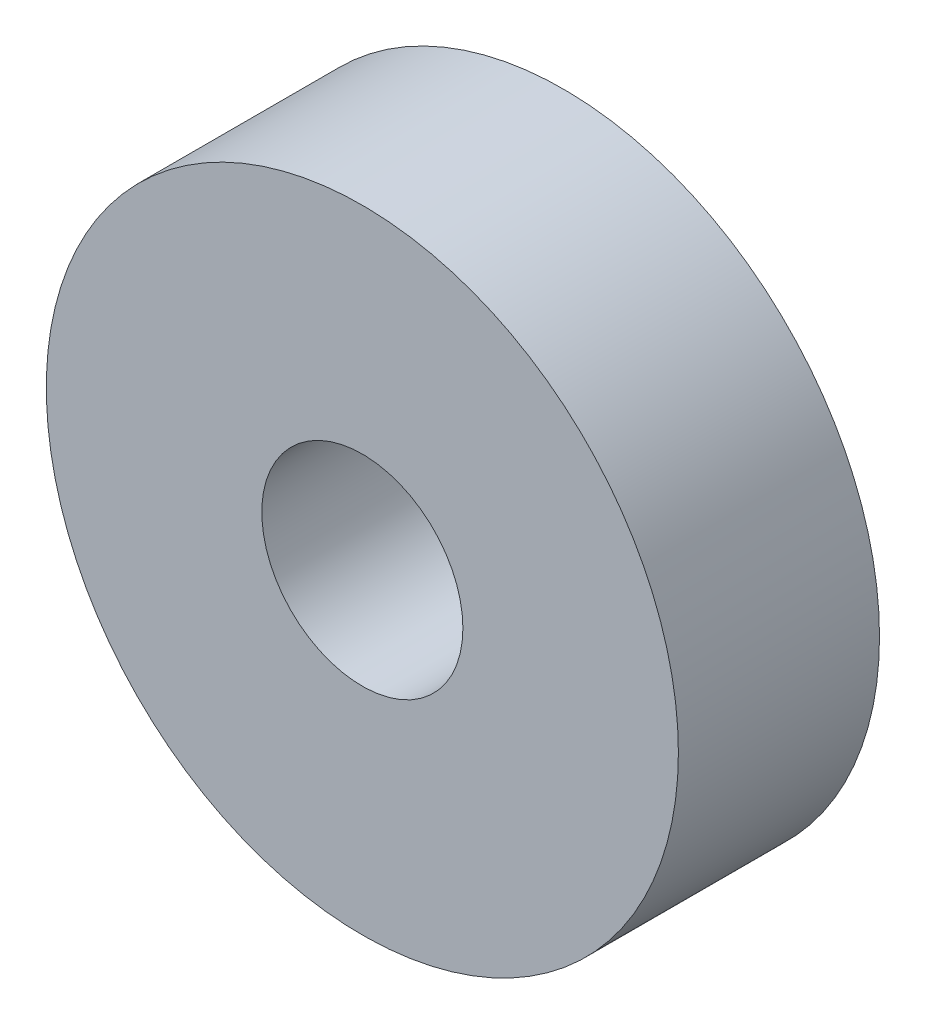
SolidWorks part; units mm, degrees
ref_plane "Front Plane" through (0, 0, 0) normal (0, 0, 1) x (1, 0, 0)
ref_plane "Top Plane" through (0, 0, 0) normal (0, 1, 0) x (1, 0, 0)
ref_plane "Right Plane" through (0, 0, 0) normal (1, 0, 0) x (0, 0, -1)
sketch "Sketch1" plane through (0, 0, 0) normal (0, 0, 1) x (1, 0, 0)
  circle A0 centre (0, 0) radius 11
  circle A1 centre (0, 0) radius 3.5
  dimension "D1" = 7
  dimension "D2" = 22
extrude "Boss-Extrude1" add sketch "Sketch1" along normal mid plane 7
